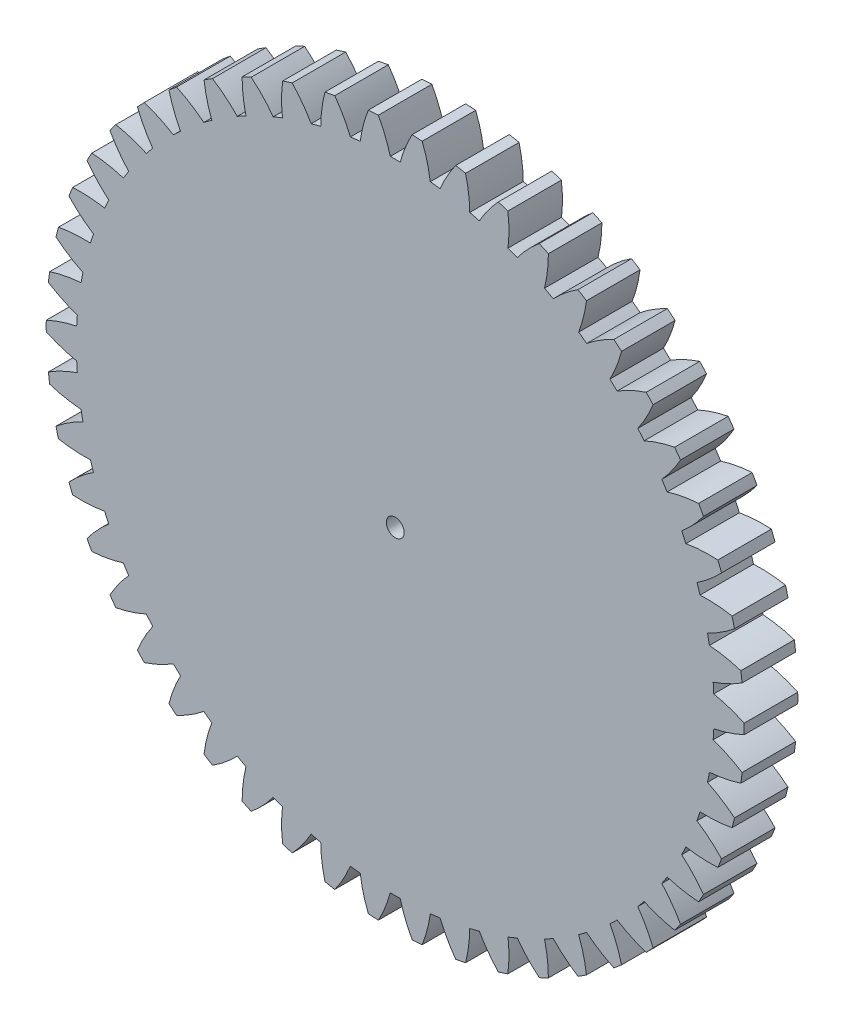
SolidWorks part; units mm, degrees
ref_plane "Front Plane" through (0, 0, 0) normal (0, 0, 1) x (1, 0, 0)
ref_plane "Top Plane" through (0, 0, 0) normal (0, 1, 0) x (1, 0, 0)
ref_plane "Right Plane" through (0, 0, 0) normal (1, 0, 0) x (0, 0, -1)
sketch "Sketch1" plane through (0, 0, 0) normal (0, 0, 1) x (1, 0, 0)
  arc A0 (6.7774, 38.5335) -> (5.0299, 35.3934) centre (19.0264, 29.6605) ccw
  arc A1 (5.0299, 35.3934) -> (3.9301, 35.5323) centre (0, 0) ccw
  arc A2 (3.9301, 35.5323) -> (3.0184, 39.0084) centre (-11.0523, 33.4604) ccw
  arc A3 (3.0184, 39.0084) -> (1.8945, 39.0791) centre (0, 0) ccw
  arc A4 (1.8945, 39.0791) -> (0.5543, 35.7447) centre (15.1589, 31.8113) ccw
  arc A5 (0.5543, 35.7447) -> (-0.5543, 35.7447) centre (0, 0) ccw
  arc A6 (-0.5543, 35.7447) -> (-1.8945, 39.0791) centre (-15.1589, 31.8113) ccw
  arc A7 (-1.8945, 39.0791) -> (-3.0184, 39.0084) centre (0, 0) ccw
  arc A8 (-3.0184, 39.0084) -> (-3.9301, 35.5323) centre (11.0523, 33.4604) ccw
  arc A9 (-3.9301, 35.5323) -> (-5.0299, 35.3934) centre (0, 0) ccw
  arc A10 (-5.0299, 35.3934) -> (-6.7774, 38.5335) centre (-19.0264, 29.6605) ccw
  arc A11 (-6.7774, 38.5335) -> (-7.8836, 38.3225) centre (0, 0) ccw
  arc A12 (-7.8836, 38.3225) -> (-8.3525, 34.7596) centre (6.7715, 34.5817) ccw
  arc A13 (-8.3525, 34.7596) -> (-9.4262, 34.4839) centre (0, 0) ccw
  arc A14 (-9.4262, 34.4839) -> (-11.5535, 37.3802) centre (-22.5938, 27.042) ccw
  arc A15 (-11.5535, 37.3802) -> (-12.6245, 37.0322) centre (0, 0) ccw
  arc A16 (-12.6245, 37.0322) -> (-12.6431, 33.4386) centre (2.3839, 35.1577) ccw
  arc A17 (-12.6431, 33.4386) -> (-13.6739, 33.0305) centre (0, 0) ccw
  arc A18 (-13.6739, 33.0305) -> (-16.1474, 35.6374) centre (-25.8049, 23.997) ccw
  arc A19 (-16.1474, 35.6374) -> (-17.1664, 35.158) centre (0, 0) ccw
  arc A20 (-17.1664, 35.158) -> (-16.7344, 31.5904) centre (-2.0414, 35.1793) ccw
  arc A21 (-16.7344, 31.5904) -> (-17.7059, 31.0563) centre (0, 0) ccw
  arc A22 (-17.7059, 31.0563) -> (-20.4866, 33.3326) centre (-28.609, 20.5736) ccw
  arc A23 (-20.4866, 33.3326) -> (-21.4375, 32.7292) centre (0, 0) ccw
  arc A24 (-21.4375, 32.7292) -> (-20.5618, 29.2439) centre (-6.4344, 34.646) ccw
  arc A25 (-20.5618, 29.2439) -> (-21.4586, 28.5923) centre (0, 0) ccw
  arc A26 (-21.4586, 28.5923) -> (-24.5028, 30.5021) centre (-30.962, 16.8257) ccw
  arc A27 (-24.5028, 30.5021) -> (-25.3705, 29.7843) centre (0, 0) ccw
  arc A28 (-25.3705, 29.7843) -> (-24.0649, 26.4362) centre (-10.726, 33.5664) ccw
  arc A29 (-24.0649, 26.4362) -> (-24.873, 25.6773) centre (0, 0) ccw
  arc A30 (-24.873, 25.6773) -> (-28.1325, 27.1906) centre (-32.8267, 12.8125) ccw
  arc A31 (-28.1325, 27.1906) -> (-28.9034, 26.3697) centre (0, 0) ccw
  arc A32 (-28.9034, 26.3697) -> (-27.1884, 23.2116) centre (-14.8484, 31.9574) ccw
  arc A33 (-27.1884, 23.2116) -> (-27.8951, 22.3574) centre (0, 0) ccw
  arc A34 (-27.8951, 22.3574) -> (-31.3186, 23.4502) centre (-34.1737, 8.5972) ccw
  arc A35 (-31.3186, 23.4502) -> (-31.9805, 22.5392) centre (0, 0) ccw
  arc A36 (-31.9805, 22.5392) -> (-29.8832, 19.621) centre (-18.7366, 29.8444) ccw
  arc A37 (-29.8832, 19.621) -> (-30.4773, 18.685) centre (0, 0) ccw
  arc A38 (-30.4773, 18.685) -> (-34.0107, 19.3401) centre (-34.9817, 4.2463) ccw
  arc A39 (-34.0107, 19.3401) -> (-34.5532, 18.3532) centre (0, 0) ccw
  arc A40 (-34.5532, 18.3532) -> (-32.1068, 15.7209) centre (-22.3294, 27.2608) ccw
  arc A41 (-32.1068, 15.7209) -> (-32.5788, 14.7178) centre (0, 0) ccw
  arc A42 (-32.5788, 14.7178) -> (-36.1665, 14.9249) centre (-35.2381, -0.1716) ccw
  arc A43 (-36.1665, 14.9249) -> (-36.581, 13.8779) centre (0, 0) ccw
  arc A44 (-36.581, 13.8779) -> (-33.8239, 11.5729) centre (-25.57, 24.2472) ccw
  arc A45 (-33.8239, 11.5729) -> (-34.1665, 10.5186) centre (0, 0) ccw
  arc A46 (-34.1665, 10.5186) -> (-37.7519, 10.2744) centre (-34.9387, -4.5867) ccw
  arc A47 (-37.7519, 10.2744) -> (-38.0319, 9.1836) centre (0, 0) ccw
  arc A48 (-38.0319, 9.1836) -> (-35.0077, 7.2424) centre (-28.4073, 20.8512) ccw
  arc A49 (-35.0077, 7.2424) -> (-35.2154, 6.1534) centre (0, 0) ccw
  arc A50 (-35.2154, 6.1534) -> (-38.7419, 5.4618) centre (-34.0883, -8.9295) ccw
  arc A51 (-38.7419, 5.4618) -> (-38.883, 4.3445) centre (0, 0) ccw
  arc A52 (-38.883, 4.3445) -> (-35.6394, 2.7976) centre (-30.7967, 17.1264) ccw
  arc A53 (-35.6394, 2.7976) -> (-35.709, 1.6912) centre (0, 0) ccw
  arc A54 (-35.709, 1.6912) -> (-39.1209, 0.5631) centre (-32.7004, -13.1315) ccw
  arc A55 (-39.1209, 0.5631) -> (-39.1209, -0.5631) centre (0, 0) ccw
  arc A56 (-39.1209, -0.5631) -> (-35.709, -1.6912) centre (-32.7004, 13.1315) ccw
  arc A57 (-35.709, -1.6912) -> (-35.6394, -2.7976) centre (0, 0) ccw
  arc A58 (-35.6394, -2.7976) -> (-38.883, -4.3445) centre (-30.7967, -17.1264) ccw
  arc A59 (-38.883, -4.3445) -> (-38.7419, -5.4618) centre (0, 0) ccw
  arc A60 (-38.7419, -5.4618) -> (-35.2154, -6.1534) centre (-34.0883, 8.9295) ccw
  arc A61 (-35.2154, -6.1534) -> (-35.0077, -7.2424) centre (0, 0) ccw
  arc A62 (-35.0077, -7.2424) -> (-38.0319, -9.1836) centre (-28.4073, -20.8512) ccw
  arc A63 (-38.0319, -9.1836) -> (-37.7519, -10.2744) centre (0, 0) ccw
  arc A64 (-37.7519, -10.2744) -> (-34.1665, -10.5186) centre (-34.9387, 4.5867) ccw
  arc A65 (-34.1665, -10.5186) -> (-33.8239, -11.5729) centre (0, 0) ccw
  arc A66 (-33.8239, -11.5729) -> (-36.581, -13.8779) centre (-25.57, -24.2472) ccw
  arc A67 (-36.581, -13.8779) -> (-36.1665, -14.9249) centre (0, 0) ccw
  arc A68 (-36.1665, -14.9249) -> (-32.5788, -14.7178) centre (-35.2381, 0.1716) ccw
  arc A69 (-32.5788, -14.7178) -> (-32.1068, -15.7209) centre (0, 0) ccw
  arc A70 (-32.1068, -15.7209) -> (-34.5532, -18.3532) centre (-22.3294, -27.2608) ccw
  arc A71 (-34.5532, -18.3532) -> (-34.0107, -19.3401) centre (0, 0) ccw
  arc A72 (-34.0107, -19.3401) -> (-30.4773, -18.685) centre (-34.9817, -4.2463) ccw
  arc A73 (-30.4773, -18.685) -> (-29.8832, -19.621) centre (0, 0) ccw
  arc A74 (-29.8832, -19.621) -> (-31.9805, -22.5392) centre (-18.7366, -29.8444) ccw
  arc A75 (-31.9805, -22.5392) -> (-31.3186, -23.4502) centre (0, 0) ccw
  arc A76 (-31.3186, -23.4502) -> (-27.8951, -22.3574) centre (-34.1737, -8.5972) ccw
  arc A77 (-27.8951, -22.3574) -> (-27.1884, -23.2116) centre (0, 0) ccw
  arc A78 (-27.1884, -23.2116) -> (-28.9034, -26.3697) centre (-14.8484, -31.9574) ccw
  arc A79 (-28.9034, -26.3697) -> (-28.1325, -27.1906) centre (0, 0) ccw
  arc A80 (-28.1325, -27.1906) -> (-24.873, -25.6773) centre (-32.8267, -12.8125) ccw
  arc A81 (-24.873, -25.6773) -> (-24.0649, -26.4362) centre (0, 0) ccw
  arc A82 (-24.0649, -26.4362) -> (-25.3705, -29.7843) centre (-10.726, -33.5664) ccw
  arc A83 (-25.3705, -29.7843) -> (-24.5028, -30.5021) centre (0, 0) ccw
  arc A84 (-24.5028, -30.5021) -> (-21.4586, -28.5923) centre (-30.962, -16.8257) ccw
  arc A85 (-21.4586, -28.5923) -> (-20.5618, -29.2439) centre (0, 0) ccw
  arc A86 (-20.5618, -29.2439) -> (-21.4375, -32.7292) centre (-6.4344, -34.646) ccw
  arc A87 (-21.4375, -32.7292) -> (-20.4866, -33.3326) centre (0, 0) ccw
  arc A88 (-20.4866, -33.3326) -> (-17.7059, -31.0563) centre (-28.609, -20.5736) ccw
  arc A89 (-17.7059, -31.0563) -> (-16.7344, -31.5904) centre (0, 0) ccw
  arc A90 (-16.7344, -31.5904) -> (-17.1664, -35.158) centre (-2.0414, -35.1793) ccw
  arc A91 (-17.1664, -35.158) -> (-16.1474, -35.6374) centre (0, 0) ccw
  arc A92 (-16.1474, -35.6374) -> (-13.6739, -33.0305) centre (-25.8049, -23.997) ccw
  arc A93 (-13.6739, -33.0305) -> (-12.6431, -33.4386) centre (0, 0) ccw
  arc A94 (-12.6431, -33.4386) -> (-12.6245, -37.0322) centre (2.3839, -35.1577) ccw
  arc A95 (-12.6245, -37.0322) -> (-11.5535, -37.3802) centre (0, 0) ccw
  arc A96 (-11.5535, -37.3802) -> (-9.4262, -34.4839) centre (-22.5938, -27.042) ccw
  arc A97 (-9.4262, -34.4839) -> (-8.3525, -34.7596) centre (0, 0) ccw
  arc A98 (-8.3525, -34.7596) -> (-7.8836, -38.3225) centre (6.7715, -34.5817) ccw
  arc A99 (-7.8836, -38.3225) -> (-6.7774, -38.5335) centre (0, 0) ccw
  arc A100 (-6.7774, -38.5335) -> (-5.0299, -35.3934) centre (-19.0264, -29.6605) ccw
  arc A101 (-5.0299, -35.3934) -> (-3.9301, -35.5323) centre (0, 0) ccw
  arc A102 (-3.9301, -35.5323) -> (-3.0184, -39.0084) centre (11.0523, -33.4604) ccw
  arc A103 (-3.0184, -39.0084) -> (-1.8945, -39.0791) centre (0, 0) ccw
  arc A104 (-1.8945, -39.0791) -> (-0.5543, -35.7447) centre (-15.1589, -31.8113) ccw
  arc A105 (-0.5543, -35.7447) -> (0.5543, -35.7447) centre (0, 0) ccw
  arc A106 (0.5543, -35.7447) -> (1.8945, -39.0791) centre (15.1589, -31.8113) ccw
  arc A107 (1.8945, -39.0791) -> (3.0184, -39.0084) centre (0, 0) ccw
  arc A108 (3.0184, -39.0084) -> (3.9301, -35.5323) centre (-11.0523, -33.4604) ccw
  arc A109 (3.9301, -35.5323) -> (5.0299, -35.3934) centre (0, 0) ccw
  arc A110 (5.0299, -35.3934) -> (6.7774, -38.5335) centre (19.0264, -29.6605) ccw
  arc A111 (6.7774, -38.5335) -> (7.8836, -38.3225) centre (0, 0) ccw
  arc A112 (7.8836, -38.3225) -> (8.3525, -34.7596) centre (-6.7715, -34.5817) ccw
  arc A113 (8.3525, -34.7596) -> (9.4262, -34.4839) centre (0, 0) ccw
  arc A114 (9.4262, -34.4839) -> (11.5535, -37.3802) centre (22.5938, -27.042) ccw
  arc A115 (11.5535, -37.3802) -> (12.6245, -37.0322) centre (0, 0) ccw
  arc A116 (12.6245, -37.0322) -> (12.6431, -33.4386) centre (-2.3839, -35.1577) ccw
  arc A117 (12.6431, -33.4386) -> (13.6739, -33.0305) centre (0, 0) ccw
  arc A118 (13.6739, -33.0305) -> (16.1474, -35.6374) centre (25.8049, -23.997) ccw
  arc A119 (16.1474, -35.6374) -> (17.1664, -35.158) centre (0, 0) ccw
  arc A120 (17.1664, -35.158) -> (16.7344, -31.5904) centre (2.0414, -35.1793) ccw
  arc A121 (16.7344, -31.5904) -> (17.7059, -31.0563) centre (0, 0) ccw
  arc A122 (17.7059, -31.0563) -> (20.4866, -33.3326) centre (28.609, -20.5736) ccw
  arc A123 (20.4866, -33.3326) -> (21.4375, -32.7292) centre (0, 0) ccw
  arc A124 (21.4375, -32.7292) -> (20.5618, -29.2439) centre (6.4344, -34.646) ccw
  arc A125 (20.5618, -29.2439) -> (21.4586, -28.5923) centre (0, 0) ccw
  arc A126 (21.4586, -28.5923) -> (24.5028, -30.5021) centre (30.962, -16.8257) ccw
  arc A127 (24.5028, -30.5021) -> (25.3705, -29.7843) centre (0, 0) ccw
  arc A128 (25.3705, -29.7843) -> (24.0649, -26.4362) centre (10.726, -33.5664) ccw
  arc A129 (24.0649, -26.4362) -> (24.873, -25.6773) centre (0, 0) ccw
  arc A130 (24.873, -25.6773) -> (28.1325, -27.1906) centre (32.8267, -12.8125) ccw
  arc A131 (28.1325, -27.1906) -> (28.9034, -26.3697) centre (0, 0) ccw
  arc A132 (28.9034, -26.3697) -> (27.1884, -23.2116) centre (14.8484, -31.9574) ccw
  arc A133 (27.1884, -23.2116) -> (27.8951, -22.3574) centre (0, 0) ccw
  arc A134 (27.8951, -22.3574) -> (31.3186, -23.4502) centre (34.1737, -8.5972) ccw
  arc A135 (31.3186, -23.4502) -> (31.9805, -22.5392) centre (0, 0) ccw
  arc A136 (31.9805, -22.5392) -> (29.8832, -19.621) centre (18.7366, -29.8444) ccw
  arc A137 (29.8832, -19.621) -> (30.4773, -18.685) centre (0, 0) ccw
  arc A138 (30.4773, -18.685) -> (34.0107, -19.3401) centre (34.9817, -4.2463) ccw
  arc A139 (34.0107, -19.3401) -> (34.5532, -18.3532) centre (0, 0) ccw
  arc A140 (34.5532, -18.3532) -> (32.1068, -15.7209) centre (22.3294, -27.2608) ccw
  arc A141 (32.1068, -15.7209) -> (32.5788, -14.7178) centre (0, 0) ccw
  arc A142 (32.5788, -14.7178) -> (36.1665, -14.9249) centre (35.2381, 0.1716) ccw
  arc A143 (36.1665, -14.9249) -> (36.581, -13.8779) centre (0, 0) ccw
  arc A144 (36.581, -13.8779) -> (33.8239, -11.5729) centre (25.57, -24.2472) ccw
  arc A145 (33.8239, -11.5729) -> (34.1665, -10.5186) centre (0, 0) ccw
  arc A146 (34.1665, -10.5186) -> (37.7519, -10.2744) centre (34.9387, 4.5867) ccw
  arc A147 (37.7519, -10.2744) -> (38.0319, -9.1836) centre (0, 0) ccw
  arc A148 (38.0319, -9.1836) -> (35.0077, -7.2424) centre (28.4073, -20.8512) ccw
  arc A149 (35.0077, -7.2424) -> (35.2154, -6.1534) centre (0, 0) ccw
  arc A150 (35.2154, -6.1534) -> (38.7419, -5.4618) centre (34.0883, 8.9295) ccw
  arc A151 (38.7419, -5.4618) -> (38.883, -4.3445) centre (0, 0) ccw
  arc A152 (38.883, -4.3445) -> (35.6394, -2.7976) centre (30.7967, -17.1264) ccw
  arc A153 (35.6394, -2.7976) -> (35.709, -1.6912) centre (0, 0) ccw
  arc A154 (35.709, -1.6912) -> (39.1209, -0.5631) centre (32.7004, 13.1315) ccw
  arc A155 (39.1209, -0.5631) -> (39.1209, 0.5631) centre (0, 0) ccw
  arc A156 (39.1209, 0.5631) -> (35.709, 1.6912) centre (32.7004, -13.1315) ccw
  arc A157 (35.709, 1.6912) -> (35.6394, 2.7976) centre (0, 0) ccw
  arc A158 (35.6394, 2.7976) -> (38.883, 4.3445) centre (30.7967, 17.1264) ccw
  arc A159 (38.883, 4.3445) -> (38.7419, 5.4618) centre (0, 0) ccw
  arc A160 (38.7419, 5.4618) -> (35.2154, 6.1534) centre (34.0883, -8.9295) ccw
  arc A161 (35.2154, 6.1534) -> (35.0077, 7.2424) centre (0, 0) ccw
  arc A162 (35.0077, 7.2424) -> (38.0319, 9.1836) centre (28.4073, 20.8512) ccw
  arc A163 (38.0319, 9.1836) -> (37.7519, 10.2744) centre (0, 0) ccw
  arc A164 (37.7519, 10.2744) -> (34.1665, 10.5186) centre (34.9387, -4.5867) ccw
  arc A165 (34.1665, 10.5186) -> (33.8239, 11.5729) centre (0, 0) ccw
  arc A166 (33.8239, 11.5729) -> (36.581, 13.8779) centre (25.57, 24.2472) ccw
  arc A167 (36.581, 13.8779) -> (36.1665, 14.9249) centre (0, 0) ccw
  arc A168 (36.1665, 14.9249) -> (32.5788, 14.7178) centre (35.2381, -0.1716) ccw
  arc A169 (32.5788, 14.7178) -> (32.1068, 15.7209) centre (0, 0) ccw
  arc A170 (32.1068, 15.7209) -> (34.5532, 18.3532) centre (22.3294, 27.2608) ccw
  arc A171 (34.5532, 18.3532) -> (34.0107, 19.3401) centre (0, 0) ccw
  arc A172 (34.0107, 19.3401) -> (30.4773, 18.685) centre (34.9817, 4.2463) ccw
  arc A173 (30.4773, 18.685) -> (29.8832, 19.621) centre (0, 0) ccw
  arc A174 (29.8832, 19.621) -> (31.9805, 22.5392) centre (18.7366, 29.8444) ccw
  arc A175 (31.9805, 22.5392) -> (31.3186, 23.4502) centre (0, 0) ccw
  arc A176 (31.3186, 23.4502) -> (27.8951, 22.3574) centre (34.1737, 8.5972) ccw
  arc A177 (27.8951, 22.3574) -> (27.1884, 23.2116) centre (0, 0) ccw
  arc A178 (27.1884, 23.2116) -> (28.9034, 26.3697) centre (14.8484, 31.9574) ccw
  arc A179 (28.9034, 26.3697) -> (28.1325, 27.1906) centre (0, 0) ccw
  arc A180 (28.1325, 27.1906) -> (24.873, 25.6773) centre (32.8267, 12.8125) ccw
  arc A181 (24.873, 25.6773) -> (24.0649, 26.4362) centre (0, 0) ccw
  arc A182 (24.0649, 26.4362) -> (25.3705, 29.7843) centre (10.726, 33.5664) ccw
  arc A183 (25.3705, 29.7843) -> (24.5028, 30.5021) centre (0, 0) ccw
  arc A184 (24.5028, 30.5021) -> (21.4586, 28.5923) centre (30.962, 16.8257) ccw
  arc A185 (21.4586, 28.5923) -> (20.5618, 29.2439) centre (0, 0) ccw
  arc A186 (20.5618, 29.2439) -> (21.4375, 32.7292) centre (6.4344, 34.646) ccw
  arc A187 (21.4375, 32.7292) -> (20.4866, 33.3326) centre (0, 0) ccw
  arc A188 (20.4866, 33.3326) -> (17.7059, 31.0563) centre (28.609, 20.5736) ccw
  arc A189 (17.7059, 31.0563) -> (16.7344, 31.5904) centre (0, 0) ccw
  arc A190 (16.7344, 31.5904) -> (17.1664, 35.158) centre (2.0414, 35.1793) ccw
  arc A191 (17.1664, 35.158) -> (16.1474, 35.6374) centre (0, 0) ccw
  arc A192 (16.1474, 35.6374) -> (13.6739, 33.0305) centre (25.8049, 23.997) ccw
  arc A193 (13.6739, 33.0305) -> (12.6431, 33.4386) centre (0, 0) ccw
  arc A194 (12.6431, 33.4386) -> (12.6245, 37.0322) centre (-2.3839, 35.1577) ccw
  arc A195 (12.6245, 37.0322) -> (11.5535, 37.3802) centre (0, 0) ccw
  arc A196 (11.5535, 37.3802) -> (9.4262, 34.4839) centre (22.5938, 27.042) ccw
  arc A197 (9.4262, 34.4839) -> (8.3525, 34.7596) centre (0, 0) ccw
  arc A198 (8.3525, 34.7596) -> (7.8836, 38.3225) centre (-6.7715, 34.5817) ccw
  arc A199 (7.8836, 38.3225) -> (6.7774, 38.5335) centre (0, 0) ccw
  circle A200 centre (0, 0) radius 1
  dimension "D1" = 2
extrude "Boss-Extrude1" add sketch "Sketch1" along normal blind 6
